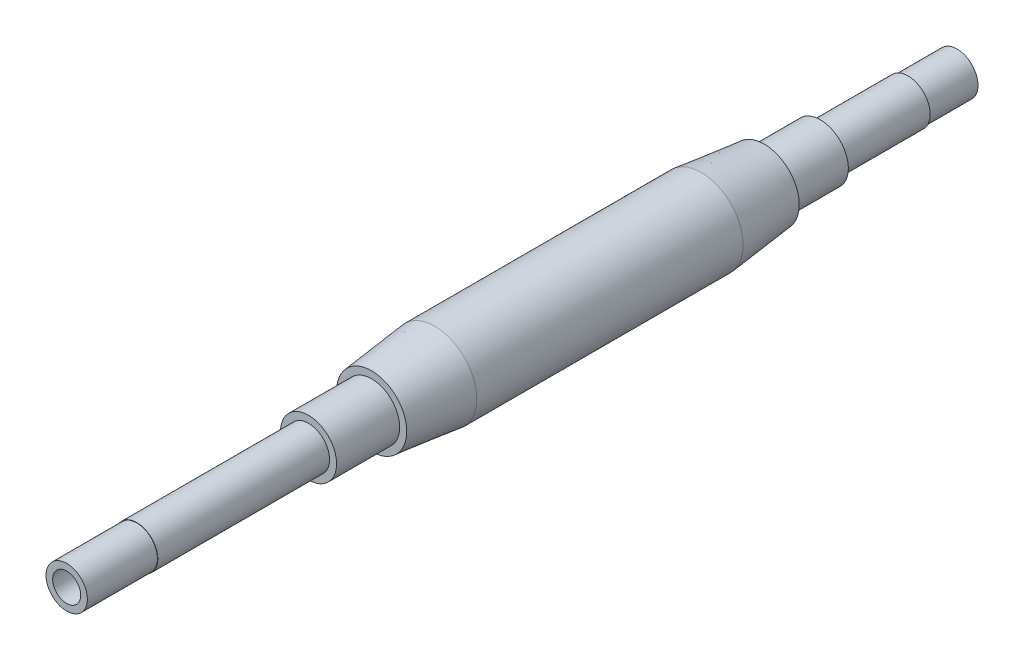
SolidWorks part; units mm, degrees
material "AISI 4340 Steel, normalized"
ref_plane "Front Plane" through (0, 0, 0) normal (0, 0, 1) x (1, 0, 0)
ref_plane "Top Plane" through (0, 0, 0) normal (0, 1, 0) x (1, 0, 0)
ref_plane "Right Plane" through (0, 0, 0) normal (1, 0, 0) x (0, 0, -1)
sketch "Sketch1" plane through (0, 0, 0) normal (1, 0, 0) x (0, 0, -1)
  line L0 (0, 0) -> (-143.0546, 0) construction
  line L1 (0, 0) -> (0, 3)
  line L2 (-7, 3.175) -> (-19.5, 3.175)
  line L3 (-19.5, 3.175) -> (-19.5, 4)
  line L4 (-19.5, 4) -> (-27.5, 4)
  line L5 (-27.5, 4) -> (-27.5, 5)
  line L6 (-27.5, 5) -> (-36.5, 6)
  line L7 (-36.5, 6) -> (-74.5, 6)
  line L8 (-74.5, 6) -> (-83.5, 5)
  line L9 (-83.5, 5) -> (-83.5, 4)
  line L10 (-83.5, 4) -> (-92.5, 4)
  line L11 (-92.5, 4) -> (-92.5, 3)
  line L12 (-92.5, 3) -> (-117, 3)
  line L13 (-127, 2.95) -> (-127, 0)
  line L14 (-127, 0) -> (0, 0)
  line L15 (0, 3) -> (-7, 3)
  line L16 (-7, 3) -> (-7, 3.175)
  line L17 (-127, 2.95) -> (-117, 2.95)
  line L18 (-117, 2.95) -> (-117, 3)
  dimension "D1" = 6
  dimension "D2" = 8
  dimension "D3" = 10
  dimension "D4" = 12
  dimension "D5" = 6
  dimension "D6" = 6.35
  dimension "D8" = 12.5
  dimension "D9" = 8
  dimension "D10" = 9
  dimension "D11" = 9
  dimension "D12" = 9
  dimension "D13" = 5.9
  dimension "D14" = 127
  dimension "D15" = 56
  dimension "D16" = 10
  dimension "D17" = 24.5
revolve "Revolve1" add sketch "Sketch1" angle 360 about L0
cosmetic thread "Cosmetic Thread1" parameters "D1"=10, "D2"=5
cosmetic thread "Cosmetic Thread2" parameters "D1"=7, "D2"=4.891
hole_wizard "Ø4.0 (4) Diameter Hole1" positions "Sketch3" profile "Sketch4" hole size "Ø4.0" standard "Ansi Metric" end condition through all
sketch "Sketch3" plane through (0, 0, 0) normal (0, 0, -1) x (-1, 0, 0)
  point P0 (0, 0)
sketch "Sketch4" plane through (0, 0, 0) normal (1, 0, 0) x (0, 1, 0)
  line L0 (0, 0) -> (0, 127)
  line L1 (0, 127) -> (2, 127)
  line L2 (2, 127) -> (2, 0)
  line L5 (2, 0) -> (0, 0)
  line L11 (0, -6.35) -> (0, 107.95) construction
  dimension "Thru Hole Dia." = 4
  dimension "Thru Hole Depth" = 127
